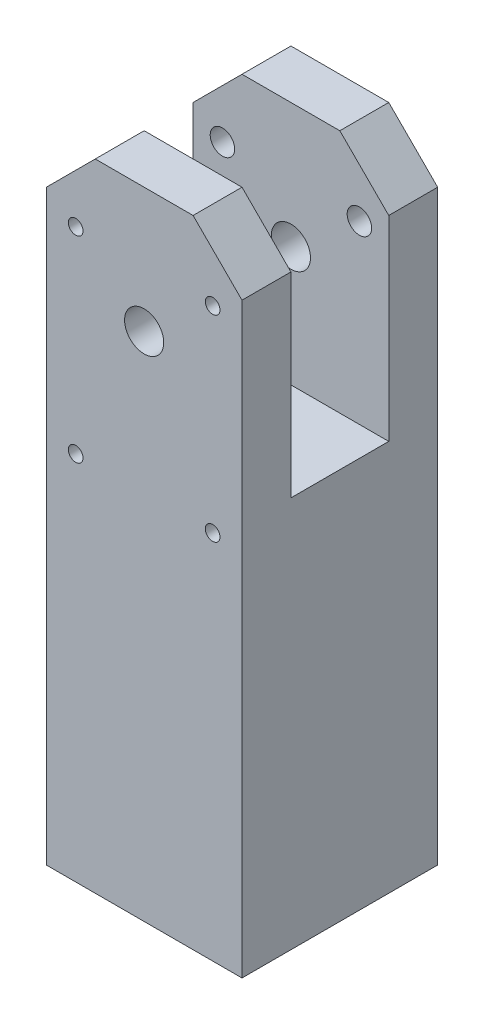
SolidWorks part; units mm, degrees
material "Nylon 6/10"
ref_plane "Front Plane" through (0, 0, 0) normal (0, 0, 1) x (1, 0, 0)
ref_plane "Top Plane" through (0, 0, 0) normal (0, 1, 0) x (1, 0, 0)
ref_plane "Right Plane" through (0, 0, 0) normal (1, 0, 0) x (0, 0, -1)
sketch "Sketch1" plane through (0, 0, 0) normal (0, 1, 0) x (1, 0, 0)
  line L1 (-156.4103, 60.0962) -> (-116.4103, 60.0962)
  line L2 (-156.4103, 60.0962) -> (-156.4103, 20.0962)
  line L3 (-156.4103, 20.0962) -> (-116.4103, 20.0962)
  line L4 (-116.4103, 60.0962) -> (-116.4103, 20.0962)
  dimension "D1" = 40
  dimension "D2" = 40
extrude "Boss-Extrude1" add sketch "Sketch1" along normal blind 80
sketch "Sketch2" plane through (0, 80, 0) normal (0, 1, 0) x (1, 0, 0)
  line L0 (-156.4103, 60.0962) -> (-116.4103, 20.0962) construction
  circle A0 centre (-136.4103, 40.0962) radius 3.5704
ref_plane "Plane1" through (-116.4103, 0, -60.0962) normal (0, 0, -1) x (-1, 0, 0)
sketch "Sketch4" plane through (0, 80, 0) normal (0, 1, 0) x (1, 0, 0)
  line L0 (-156.4103, 60.0962) -> (-156.4103, 20.0962) construction
  line L1 (-156.4103, 30.0962) -> (-116.4103, 30.0962)
  line L2 (-156.4103, 30.0962) -> (-156.4103, 20.0962)
  line L3 (-156.4103, 20.0962) -> (-116.4103, 20.0962)
  line L4 (-116.4103, 30.0962) -> (-116.4103, 20.0962)
  line L5 (-116.4103, 20.0962) -> (-116.4103, 60.0962) construction
  line L6 (-156.4103, 60.0962) -> (-116.4103, 60.0962)
  line L7 (-156.4103, 60.0962) -> (-156.4103, 50.0962)
  line L8 (-156.4103, 50.0962) -> (-116.4103, 50.0962)
  line L9 (-116.4103, 60.0962) -> (-116.4103, 50.0962)
  dimension "D1" = 10
  dimension "D2" = 10
extrude "Boss-Extrude2" add sketch "Sketch4" along normal blind 50
chamfer "Chamfer1" distance 10 angle 45 4 edges at (-116.4103, 130, -25.0962) (-116.4103, 130, -55.0962) (-156.4103, 130, -55.0962) (-156.4103, 130, -25.0962)
sketch "Sketch5" plane through (0, 0, -60.0962) normal (0, 0, -1) x (-1, 0, 0)
  circle A0 centre (136.4103, 104.4798) radius 4
  point P2 (136.4103, 104.4798)
  dimension "D1" = 8
  dimension "D2" = 0
extrude "Cut-Extrude1" cut sketch "Sketch5" against normal blind 60
sketch "Sketch6" plane through (0, 0, -20.0962) normal (0, 0, 1) x (1, 0, 0)
  circle A0 centre (-150.4103, 75.8) radius 1.5
  circle A1 centre (-150.4103, 116) radius 1.5
  circle A2 centre (-122.4103, 116) radius 1.5
  circle A3 centre (-122.4103, 75.8) radius 1.5
extrude "Cut-Extrude2" cut sketch "Sketch6" against normal blind 60
sketch "Sketch7" plane through (0, 0, -60.0962) normal (0, 0, -1) x (-1, 0, 0)
  circle A0 centre (150.4103, 116) radius 2.5
  circle A1 centre (122.4103, 116) radius 2.5
  dimension "D1" = 5
  dimension "D2" = 5
chamfer "Chamfer2" distance 2 angle 45 2 edges at (-148.9103, 116, -30.0962) (-120.9103, 116, -30.0962)
extrude "Cut-Extrude3" cut sketch "Sketch7" against normal blind 20
